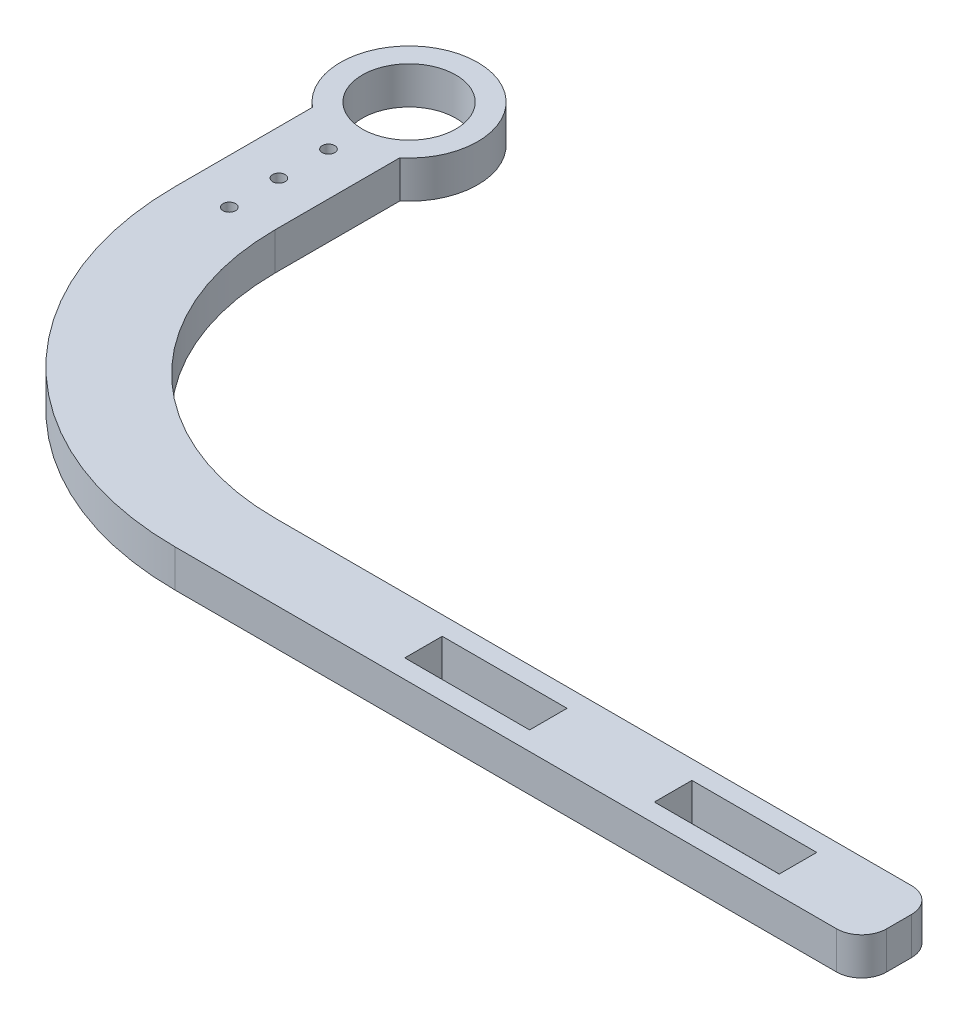
SolidWorks part; units mm, degrees
ref_plane "Front Plane" through (0, 0, 0) normal (0, 0, 1) x (1, 0, 0)
ref_plane "Top Plane" through (0, 0, 0) normal (0, 1, 0) x (1, 0, 0)
ref_plane "Right Plane" through (0, 0, 0) normal (1, 0, 0) x (0, 0, -1)
sketch "Sketch1" plane through (0, 0, 0) normal (0, 1, 0) x (1, 0, 0)
  line L1 (-50, 25) -> (50, 25)
  line L2 (-50, 25) -> (-50, -25)
  line L3 (-50, -25) -> (50, -25)
  line L4 (50, 25) -> (50, -25)
  line L5 (-50, 25) -> (50, -25) construction
  line L6 (-50, -25) -> (50, 25) construction
  point P0 (0, 0)
  dimension "D1" = 100
  dimension "D2" = 50
extrude "Boss-Extrude1" add sketch "Sketch1" along normal blind 3
sketch "Sketch3" plane through (0, 3, 0) normal (0, 1, 0) x (1, 0, 0)
  line L0 (-40.8266, 13.5904) -> (-40.8266, -16.4096)
  line L1 (-40.8266, -16.4096) -> (32.1734, -16.4096)
  line L2 (32.1734, -16.4096) -> (32.1734, -22.4096)
  line L3 (32.1734, -22.4096) -> (-47.8266, -22.4096)
  line L4 (-47.8266, -22.4096) -> (-47.8266, 13.5904)
  line L5 (32.1734, -19.4096) -> (-65.6084, -19.4096) construction
  line L6 (-50, -25) -> (50, -25) construction
  line L11 (9.0734, 0) -> (9.0734, -22.4096) construction
  line L12 (9.0734, -22.4096) -> (9.0734, -28.6262) construction
  line L13 (-5.9266, -20.9096) -> (4.0734, -20.9096)
  line L14 (-5.9266, -20.9096) -> (-5.9266, -17.9096)
  line L15 (-5.9266, -17.9096) -> (4.0734, -17.9096)
  line L16 (4.0734, -20.9096) -> (4.0734, -17.9096)
  line L17 (-5.9266, -20.9096) -> (4.0734, -17.9096) construction
  line L18 (-5.9266, -17.9096) -> (4.0734, -20.9096) construction
  line L19 (14.0734, -17.9065) -> (24.0734, -17.9065)
  line L20 (14.0734, -17.9065) -> (14.0734, -20.9126)
  line L21 (14.0734, -20.9126) -> (24.0734, -20.9126)
  line L22 (24.0734, -17.9065) -> (24.0734, -20.9126)
  line L23 (14.0734, -17.9065) -> (24.0734, -20.9126) construction
  line L24 (14.0734, -20.9126) -> (24.0734, -17.9065) construction
  line L25 (-50, 25) -> (50, 25)
  line L26 (-50, 25) -> (-50, -25)
  line L27 (-50, -25) -> (50, -25)
  line L28 (50, 25) -> (50, -25)
  line L29 (50, -25) -> (50, 25) construction
  arc A0 (-47.8266, 13.5904) -> (-40.8266, 13.5904) centre (-44.3266, 17.8331) cw
  point P10 (-20.7767, -19.4096)
  point P15 (-0.9266, -19.4096)
  point P20 (20.5401, -19.8505)
  line M8 (50, -25) -> (50, 25)
  line M9 (50, 25) -> (-50, 25)
  line M10 (-50, 25) -> (-50, -25)
  line M11 (-50, -25) -> (50, -25)
  dimension "D2" = 5.5
  dimension "D1" = 6
  dimension "D3" = 80
  dimension "D4" = 7
  dimension "D5" = 56.9
  dimension "D6" = 5
  dimension "D7" = 5
  dimension "D8" = 10
  dimension "D9" = 10
  dimension "D10" = 30
extrude "Cut-Extrude4" cut sketch "Sketch3" against normal blind 10 contours L4 A0 L0 L1 L2 L3 M11 M8 M9 M10
sketch "Sketch4" plane through (0, 3, 0) normal (0, 1, 0) x (1, 0, 0)
  circle A0 centre (-44.3266, 17.8331) radius 1.7985
extrude "Cut-Extrude5" cut sketch "Sketch4" against normal blind 10
fillet "Fillet1" radius 20 1 edges at (-40.8266, 1.5, 16.4096)
fillet "Fillet2" radius 25 1 edges at (-47.8266, 1.5, 22.4096)
sketch "Sketch7" plane through (0, 3, 0) normal (0, 1, 0) x (1, 0, 0)
  circle A0 centre (-44.2831, 11.3332) radius 0.5
  circle A1 centre (-44.2564, 7.3333) radius 0.5
  circle A2 centre (-44.2297, 3.3334) radius 0.5
  circle A3 centre (-44.3266, 17.8331) radius 3.75
  dimension "D1" = 7.5
extrude "Cut-Extrude7" cut sketch "Sketch7" against normal blind 10
fillet "Fillet3" radius 2 2 edges at (32.1734, 1.5, 22.4096) (32.1734, 1.5, 16.4096)
